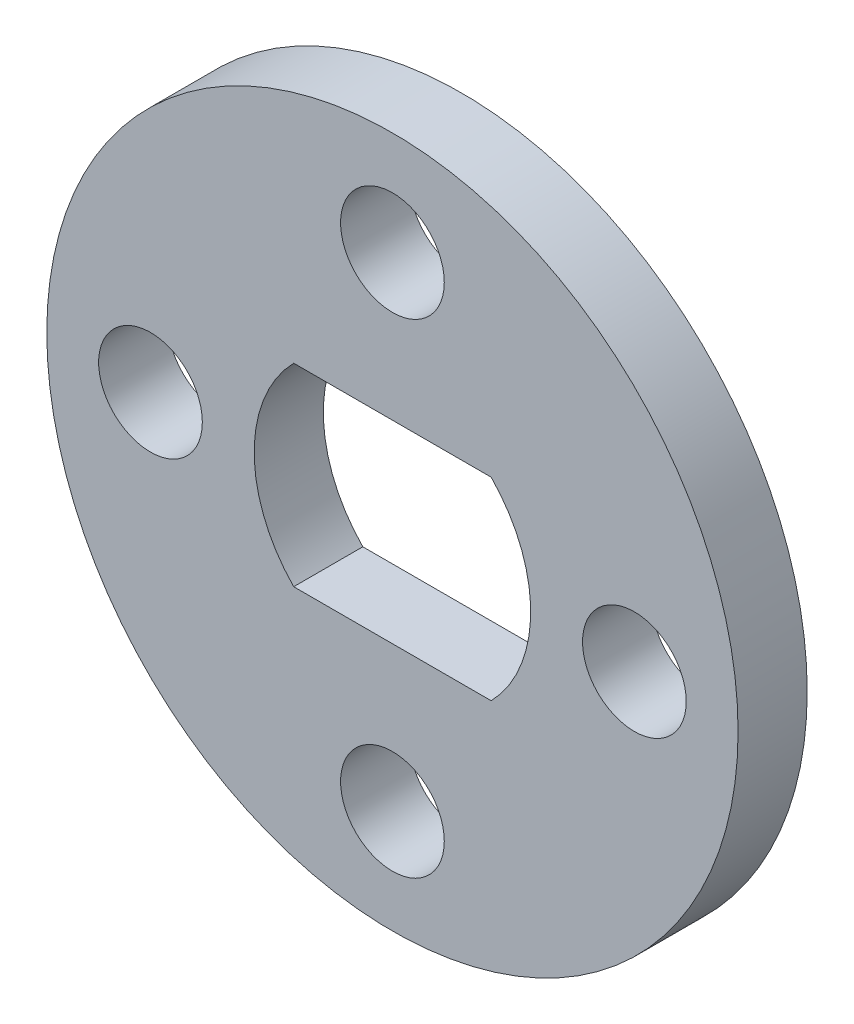
SolidWorks part; units mm, degrees
ref_plane "前视基准面" through (0, 0, 0) normal (0, 0, 1) x (1, 0, 0)
ref_plane "上视基准面" through (0, 0, 0) normal (0, 1, 0) x (1, 0, 0)
ref_plane "右视基准面" through (0, 0, 0) normal (1, 0, 0) x (0, 0, -1)
sketch "草图1" plane through (0, 0, 0) normal (0, 0, 1) x (1, 0, 0)
  circle A1 centre (0, 0) radius 10
  circle A3 centre (0, 7) radius 1.5
  circle A4 centre (7, 0) radius 1.5
  circle A5 centre (-7, 0) radius 1.5
  circle A6 centre (0, -7) radius 1.5
extrude "凸台-拉伸1" add sketch "草图1" along normal blind 2
sketch "草图2" plane through (0, 0, 0) normal (0, 0, -1) x (-1, 0, 0)
  line L9 (-2.6885, -2.8) -> (2.6885, -2.8)
  line L10 (-2.8566, 2.8) -> (2.8566, 2.8)
  line L14 (-2.8566, -2.8) -> (2.8566, -2.8)
  arc A1 (-2.8566, 2.8) -> (-2.8566, -2.8) centre (0, 0) ccw
  arc A2 (2.8566, 2.8) -> (2.8566, -2.8) centre (0, 0) cw
extrude "切除-拉伸1" cut sketch "草图2" against normal through all contours A2 L10 A1 L9
